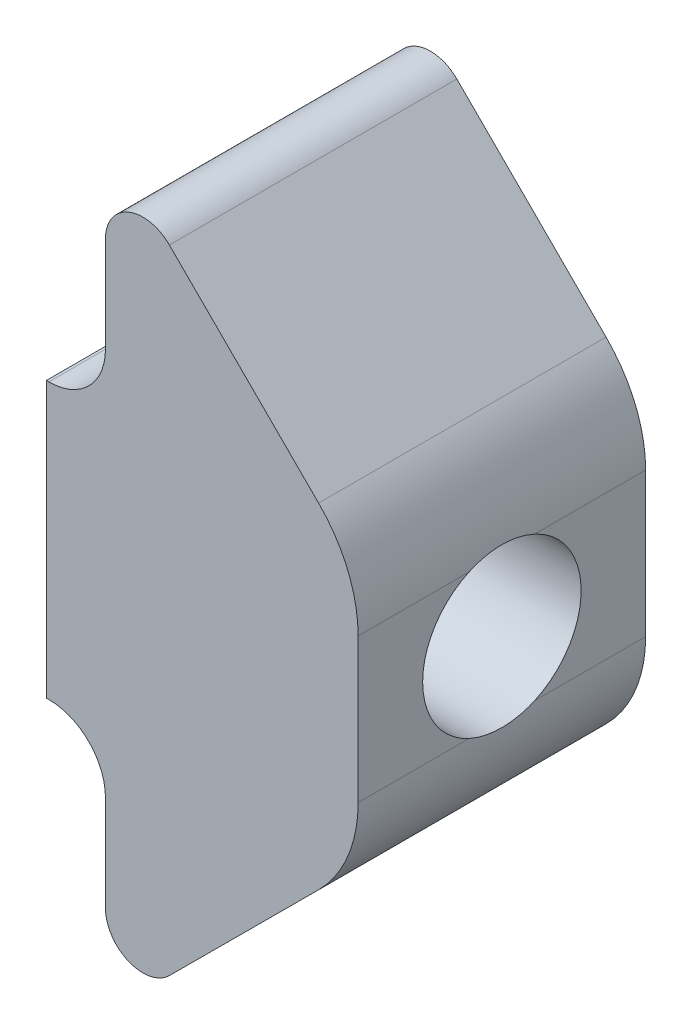
SolidWorks part; units mm, degrees
ref_plane "Front Plane" through (0, 0, 0) normal (0, 0, 1) x (1, 0, 0)
ref_plane "Top Plane" through (0, 0, 0) normal (0, 1, 0) x (1, 0, 0)
ref_plane "Right Plane" through (0, 0, 0) normal (1, 0, 0) x (0, 0, -1)
sketch "Sketch1" plane through (0, 0, 0) normal (0, 0, 1) x (1, 0, 0)
  line L0 (-11.5951, -3.0385) -> (-11.5951, 3.0385)
  line L1 (-11.5951, 3.0385) -> (-11.5392, 3.0385)
  line L2 (-10.2902, 4.2875) -> (-10.2902, 6.4021)
  line L3 (-8.8784, 6.9878) -> (-5.5823, 3.6992)
  line L4 (-4.7085, 1.5932) -> (-4.7085, -1.5932)
  line L5 (-5.5823, -3.6992) -> (-8.8784, -6.9878)
  line L6 (-10.2902, -6.4021) -> (-10.2902, -4.2875)
  line L7 (-11.5392, -3.0385) -> (-11.5951, -3.0385)
  line L8 (-11.651, 3.0385) -> (-11.5392, 3.0385) construction
  line L9 (-11.5392, -3.0385) -> (-11.651, -3.0385) construction
  line L10 (-11.5951, -3.0385) -> (-11.9739, -3.0385)
  line L119 (-11.651, 3.2385) -> (-11.5392, 3.2385) construction
  line L120 (-10.4902, 4.2875) -> (-10.4902, 6.4021) construction
  line L121 (-8.7371, 7.1294) -> (-5.441, 3.8408) construction
  line L122 (-4.5085, 1.5932) -> (-4.5085, -1.5932) construction
  line L123 (-5.441, -3.8408) -> (-8.7371, -7.1294) construction
  line L124 (-10.4902, -6.4021) -> (-10.4902, -4.2875) construction
  line L125 (-11.5392, -3.2385) -> (-11.651, -3.2385) construction
  arc A0 (-11.5392, 3.0385) -> (-10.2902, 4.2875) centre (-11.5392, 4.2875) ccw
  arc A1 (-8.8784, 6.9878) -> (-10.2902, 6.4021) centre (-9.4628, 6.4021) ccw
  arc A2 (-4.7085, 1.5932) -> (-5.5823, 3.6992) centre (-7.6835, 1.5932) ccw
  arc A3 (-5.5823, -3.6992) -> (-4.7085, -1.5932) centre (-7.6835, -1.5932) ccw
  arc A4 (-10.2902, -6.4021) -> (-8.8784, -6.9878) centre (-9.4628, -6.4021) ccw
  arc A5 (-10.2902, -4.2875) -> (-11.5392, -3.0385) centre (-11.5392, -4.2875) ccw
  arc A142 (-11.5392, 3.2385) -> (-10.4902, 4.2875) centre (-11.5392, 4.2875) ccw construction
  arc A143 (-8.7371, 7.1294) -> (-10.4902, 6.4021) centre (-9.4628, 6.4021) ccw construction
  arc A144 (-4.5085, 1.5932) -> (-5.441, 3.8408) centre (-7.6835, 1.5932) ccw construction
  arc A145 (-5.441, -3.8408) -> (-4.5085, -1.5932) centre (-7.6835, -1.5932) ccw construction
  arc A146 (-10.4902, -6.4021) -> (-8.7371, -7.1294) centre (-9.4628, -6.4021) ccw construction
  arc A147 (-10.4902, -4.2875) -> (-11.5392, -3.2385) centre (-11.5392, -4.2875) ccw construction
  dimension "D1" = 0.2
  dimension "D2" = 6.0769
  dimension "D3" = 0.3788
extrude "Boss-Extrude1" add sketch "Sketch1" along normal blind 6.35 contours L0 L1 A0 L2 A1 L3 A2 L4 A3 L5 A4 L6 A5 L7
sketch "Sketch2" plane through (-11.5951, 0, 0) normal (-1, 0, 0) x (0, 0, 1)
  line L0 (3.175, 3.0385) -> (3.175, -3.0385) construction
  line L1 (6.35, 3.0385) -> (0, 3.0385) construction
  line L2 (6.35, -3.0385) -> (0, -3.0385) construction
  line L3 (0, 0) -> (6.35, 0) construction
  line L4 (0, -3.0385) -> (0, 3.0385) construction
  line L5 (6.35, -3.0385) -> (6.35, 3.0385) construction
  circle A0 centre (3.175, 0) radius 1.75
  dimension "D1" = 3.5
extrude "Cut-Extrude1" cut sketch "Sketch2" against normal up to next contours A0
fillet "Fillet1" radius 0.2 1 edges at (-11.5951, 0, 4.925)
